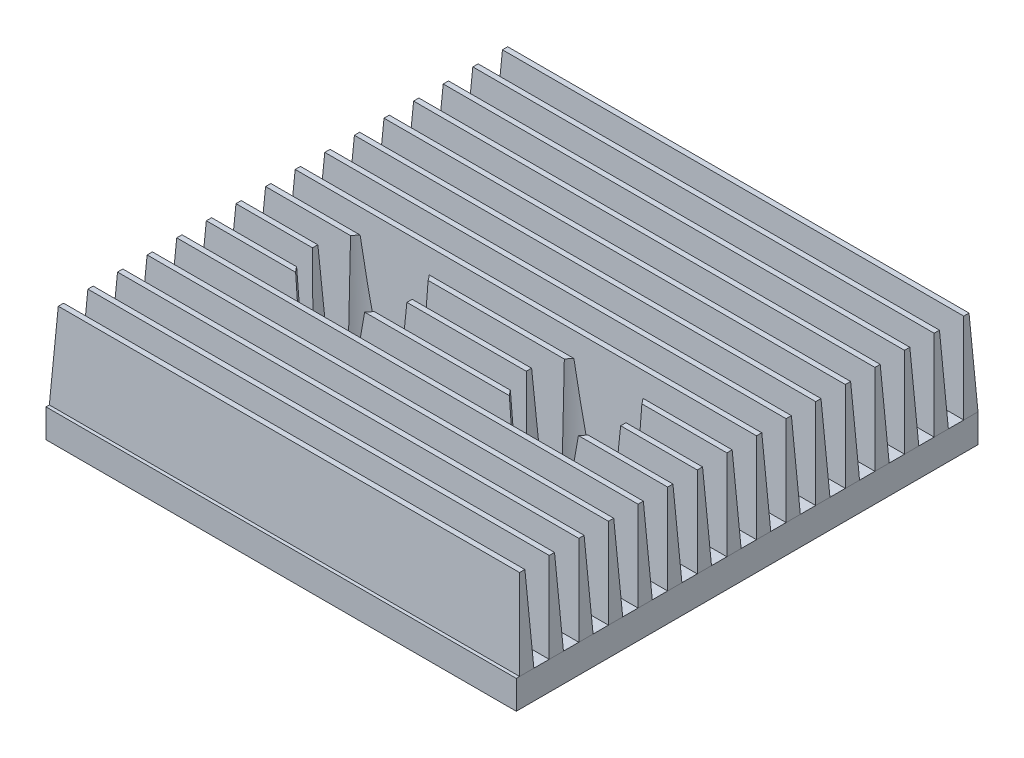
SolidWorks part; units mm, degrees
ref_plane "Front Plane" through (0, 0, 0) normal (0, 0, 1) x (1, 0, 0)
ref_plane "Top Plane" through (0, 0, 0) normal (0, 1, 0) x (1, 0, 0)
ref_plane "Right Plane" through (0, 0, 0) normal (1, 0, 0) x (0, 0, -1)
sketch "Sketch1" plane through (0, 0, 0) normal (0, 1, 0) x (1, 0, 0)
  line L0 (-20.955, 0) -> (-9.525, 0) construction
  line L1 (-20.955, -24.384) -> (20.955, -24.384)
  line L2 (-20.955, -24.384) -> (-20.955, 24.384)
  line L3 (-20.955, 24.384) -> (20.955, 24.384)
  line L4 (20.955, -24.384) -> (20.955, 24.384)
  line L5 (-20.955, -24.384) -> (20.955, 24.384) construction
  line L6 (-20.955, 24.384) -> (20.955, -24.384) construction
  line L7 (-9.525, 0) -> (9.525, 0) construction
  line L8 (9.525, 0) -> (20.955, 0) construction
  circle A0 centre (9.525, 0) radius 1.5
  circle A1 centre (-9.525, 0) radius 1.5
  point P0 (0, 0)
  dimension "D4" = 3
  dimension "D1" = 41.91
  dimension "D2" = 48.768
  dimension "D3" = 11.43
extrude "Boss-Extrude1" add sketch "Sketch1" along normal blind 2.54 contours L1 L4 L3 L2 A1 A0
sketch "Sketch2" plane through (0, 2.54, 0) normal (0, 1, 0) x (1, 0, 0)
  line L0 (-20.955, 24.384) -> (20.955, 24.384)
  line L1 (20.955, 24.384) -> (20.955, 23.114)
  line L3 (20.955, 23.114) -> (-20.955, 23.114)
  line L5 (-20.955, 23.114) -> (-20.955, 24.384)
  line L6 (20.955, 20.4752) -> (-20.955, 20.4752)
  line L7 (-20.955, 20.4752) -> (-20.955, 21.7452)
  line L8 (-20.955, 21.7452) -> (20.955, 21.7452)
  line L9 (20.955, 21.7452) -> (20.955, 20.4752)
  line L10 (20.955, 17.8364) -> (-20.955, 17.8364)
  line L11 (-20.955, 17.8364) -> (-20.955, 19.1064)
  line L12 (-20.955, 19.1064) -> (20.955, 19.1064)
  line L13 (20.955, 19.1064) -> (20.955, 17.8364)
  line L14 (20.955, 15.1977) -> (-20.955, 15.1977)
  line L15 (-20.955, 15.1977) -> (-20.955, 16.4677)
  line L16 (-20.955, 16.4677) -> (20.955, 16.4677)
  line L17 (20.955, 16.4677) -> (20.955, 15.1977)
  line L18 (20.955, 12.5589) -> (-20.955, 12.5589)
  line L19 (-20.955, 12.5589) -> (-20.955, 13.8289)
  line L20 (-20.955, 13.8289) -> (20.955, 13.8289)
  line L21 (20.955, 13.8289) -> (20.955, 12.5589)
  line L22 (20.955, 9.9201) -> (-20.955, 9.9201)
  line L23 (-20.955, 9.9201) -> (-20.955, 11.1901)
  line L24 (-20.955, 11.1901) -> (20.955, 11.1901)
  line L25 (20.955, 11.1901) -> (20.955, 9.9201)
  line L26 (20.955, 7.2813) -> (-20.955, 7.2813)
  line L27 (-20.955, 7.2813) -> (-20.955, 8.5513)
  line L28 (-20.955, 8.5513) -> (20.955, 8.5513)
  line L29 (20.955, 8.5513) -> (20.955, 7.2813)
  line L30 (20.955, 4.6426) -> (-20.955, 4.6426)
  line L31 (-20.955, 4.6426) -> (-20.955, 5.9126)
  line L32 (-20.955, 5.9126) -> (20.955, 5.9126)
  line L33 (20.955, 5.9126) -> (20.955, 4.6426)
  line L34 (20.955, 2.0038) -> (-20.955, 2.0038)
  line L35 (-20.955, 2.0038) -> (-20.955, 3.2738)
  line L36 (-20.955, 3.2738) -> (20.955, 3.2738)
  line L37 (20.955, 3.2738) -> (20.955, 2.0038)
  line L38 (20.955, -0.635) -> (-20.955, -0.635)
  line L39 (-20.955, -0.635) -> (-20.955, 0.635)
  line L40 (-20.955, 0.635) -> (20.955, 0.635)
  line L41 (20.955, 0.635) -> (20.955, -0.635)
  line L42 (20.955, -3.2738) -> (-20.955, -3.2738)
  line L43 (-20.955, -3.2738) -> (-20.955, -2.0038)
  line L44 (-20.955, -2.0038) -> (20.955, -2.0038)
  line L45 (20.955, -2.0038) -> (20.955, -3.2738)
  line L46 (20.955, -5.9126) -> (-20.955, -5.9126)
  line L47 (-20.955, -5.9126) -> (-20.955, -4.6426)
  line L48 (-20.955, -4.6426) -> (20.955, -4.6426)
  line L49 (20.955, -4.6426) -> (20.955, -5.9126)
  line L50 (20.955, -8.5513) -> (-20.955, -8.5513)
  line L51 (-20.955, -8.5513) -> (-20.955, -7.2813)
  line L52 (-20.955, -7.2813) -> (20.955, -7.2813)
  line L53 (20.955, -7.2813) -> (20.955, -8.5513)
  line L54 (20.955, -11.1901) -> (-20.955, -11.1901)
  line L55 (-20.955, -11.1901) -> (-20.955, -9.9201)
  line L56 (-20.955, -9.9201) -> (20.955, -9.9201)
  line L57 (20.955, -9.9201) -> (20.955, -11.1901)
  line L58 (20.955, -13.8289) -> (-20.955, -13.8289)
  line L59 (-20.955, -13.8289) -> (-20.955, -12.5589)
  line L60 (-20.955, -12.5589) -> (20.955, -12.5589)
  line L61 (20.955, -12.5589) -> (20.955, -13.8289)
  line L62 (20.955, -16.4677) -> (-20.955, -16.4677)
  line L63 (-20.955, -16.4677) -> (-20.955, -15.1977)
  line L64 (-20.955, -15.1977) -> (20.955, -15.1977)
  line L65 (20.955, -15.1977) -> (20.955, -16.4677)
  line L66 (20.955, -19.1064) -> (-20.955, -19.1064)
  line L67 (-20.955, -19.1064) -> (-20.955, -17.8364)
  line L68 (-20.955, -17.8364) -> (20.955, -17.8364)
  line L69 (20.955, -17.8364) -> (20.955, -19.1064)
  line L70 (20.955, -21.7452) -> (-20.955, -21.7452)
  line L71 (-20.955, -21.7452) -> (-20.955, -20.4752)
  line L72 (-20.955, -20.4752) -> (20.955, -20.4752)
  line L73 (20.955, -20.4752) -> (20.955, -21.7452)
  line L74 (20.955, -24.384) -> (-20.955, -24.384)
  line L75 (-20.955, -24.384) -> (-20.955, -23.114)
  line L76 (-20.955, -23.114) -> (20.955, -23.114)
  line L77 (20.955, -23.114) -> (20.955, -24.384)
  line L79 (20.955, -24.384) -> (20.955, 24.384) construction
  line L80 (-20.955, -24.384) -> (-20.955, 24.384) construction
  line L81 (-20.955, -24.384) -> (20.955, -24.384) construction
  circle A0 centre (-9.525, 0) radius 3.81
  circle A1 centre (9.525, 0) radius 3.81
  dimension "D3" = 7.62
  dimension "D1" = 1.27
  dimension "D2" = 19
extrude "Boss-Extrude2" add sketch "Sketch2" along normal blind 7.62 draft 3 contours L77 L76 L75 L74 | L73 L72 L71 L70 | L69 L68 L67 L66 | L65 L64 L63 L62 | L61 L60 L59 L58 | L57 L56 L55 L54 | L49 L48 L47 L46 | A0 L44 L43 L42 | A0 L40 L39 L38 | A0 L36 L35 L34 | L33 L32 L31 L30 | L29 L28 L27 L26 | L25 L24 L23 L22 | L21 L20 L19 L18 | L17 L16 L15 L14 | L13 L12 L11 L10 | L9 L8 L7 L6 | L5 L3 L1 L0 | A1 L36 A0 L34 | A1 L40 A0 L38 | A1 L44 A0 L42 | A1 L42 L45 L44 | A1 L38 L41 L40 | A1 L34 L37 L36 | L50 L51 L52 L53
sketch "Sketch3" plane through (0, 2.54, 0) normal (0, 1, 0) x (1, 0, 0)
  line L0 (-20.955, -16.764) -> (20.955, -16.764)
  line L1 (-20.955, -17.8364) -> (-20.955, -16.4677) construction
  line L2 (20.955, -17.8364) -> (20.955, -16.4677) construction
  line L3 (20.955, -16.764) -> (20.955, -24.384)
  line L4 (20.955, -24.384) -> (-20.955, -24.384)
  line L5 (-20.955, -24.384) -> (-20.955, -16.764)
  dimension "D1" = 7.62
extrude "Cut-Extrude1" cut sketch "Sketch3" against normal through all both and the other way through all
